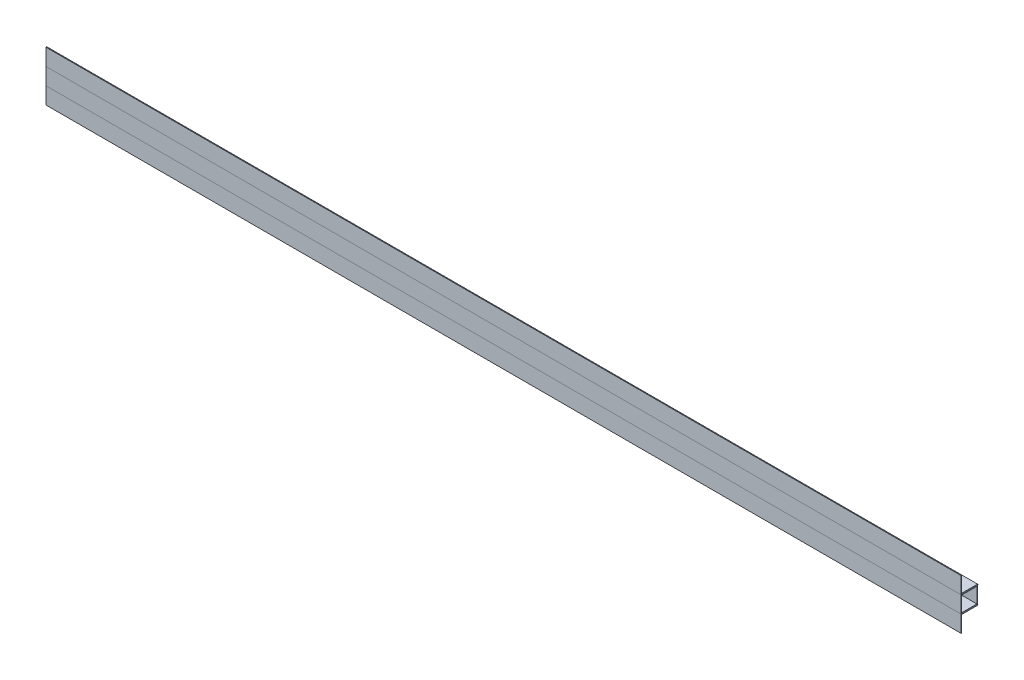
SolidWorks part; units mm, degrees
ref_plane "Front Plane" through (0, 0, 0) normal (0, 0, 1) x (1, 0, 0)
ref_plane "Top Plane" through (0, 0, 0) normal (0, 1, 0) x (1, 0, 0)
ref_plane "Right Plane" through (0, 0, 0) normal (1, 0, 0) x (0, 0, -1)
sketch3d "3DSketch1"
  line L0 (0, 0, 0) -> (1392.0499, 0, 0)
  dimension "D1" = 1392.0499
other "Squre tube 1X1SQUARE TUBE(1)"
ref_plane "Plane1" through (0, 0, 0) normal (1, 0, 0) x (0, 0, -1)
sketch "Sketch1" plane through (0, 0, 0) normal (1, 0, 0) x (0, 0, -1)
  line L0 (-11.7, 11.7) -> (11.7, 11.7)
  line L1 (-12.7, 12.7) -> (12.7, 12.7)
  line L2 (-12.7, 12.7) -> (-12.7, -12.7)
  line L3 (-12.7, -12.7) -> (12.7, -12.7)
  line L4 (12.7, 12.7) -> (12.7, -12.7)
  line L5 (0, -12.7) -> (0, 12.7) construction
  line L6 (-12.7, 0) -> (12.7, 0) construction
  line L7 (11.7, 11.7) -> (11.7, -11.7)
  line L8 (-11.7, -11.7) -> (11.7, -11.7)
  line L9 (-11.7, 11.7) -> (-11.7, -11.7)
  point P0 (0, 0)
  point P8 (0, 0)
  point P9 (0, -12.7)
  point P10 (0, 12.7)
  point P11 (0, 0)
  dimension "D1" = 25.4
  dimension "D2" = 25.4
  dimension "D3" = 1
ref_plane "Plane2" through (0, 12.7, 0) normal (0, 1, 0) x (1, 0, 0)
sketch3d "3DSketch3"
  line L0 (0, 12.7, 0) -> (1392.0499, 12.7, 0)
  line L1 (0, 12.7, -12.7) -> (0, 12.7, 12.7) construction
  line L2 (1392.0499, 12.7, -12.7) -> (1392.0499, 12.7, 12.7) construction
other "Angleiron ANGLE IRON ONE BY ONE INCH 2ND FILE(1)"
ref_plane "Plane3" through (0, 12.7, 12.7) normal (1, 0, 0) x (0, 0, -1)
sketch "Sketch13" plane through (0, 12.7, 12.7) normal (1, 0, 0) x (0, 0, -1)
  line L0 (1.25, 25.4) -> (1.25, 1.25)
  line L1 (1.25, 1.25) -> (25.4, 1.25)
  line L3 (25.4, 0) -> (0, 0)
  line L4 (0, 0) -> (0, 25.4)
  line L6 (0.625, 26.025) -> (0, 25.4)
  line L7 (0.625, 26.025) -> (1.25, 25.4)
  line L10 (26.025, 0.625) -> (25.4, 1.25)
  line L11 (26.025, 0.625) -> (25.4, 0)
  point P0 (12.7, 0)
  point P2 (0, 12.7)
  point P4 (0, 0)
  dimension "D1" = 90
  dimension "D2" = 90
  dimension "D3" = 1.25
  dimension "D4" = 1.25
  dimension "D5" = 25.4
  dimension "D6" = 25.4
sketch3d "3DSketch4"
  line L0 (0, -12.7, 0) -> (1392.0499, -12.7, 0)
  line L1 (1392.0499, -12.7, 12.7) -> (1392.0499, -12.7, -12.7) construction
other "Angleiron ANGLE IRON ONE BY ONE INCH 2ND FILE(2)"
ref_plane "Plane4" through (0, -12.7, 12.7) normal (-1, 0, 0) x (0, 0, -1)
sketch "Sketch14" plane through (0, -12.7, 12.7) normal (-1, 0, 0) x (0, 0, -1)
  line L0 (1.25, 25.4) -> (1.25, 1.25)
  line L1 (1.25, 1.25) -> (25.4, 1.25)
  line L3 (25.4, 0) -> (0, 0)
  line L4 (0, 0) -> (0, 25.4)
  line L6 (0.625, 26.025) -> (0, 25.4)
  line L7 (0.625, 26.025) -> (1.25, 25.4)
  line L10 (26.025, 0.625) -> (25.4, 1.25)
  line L11 (26.025, 0.625) -> (25.4, 0)
  point P0 (12.7, 0)
  point P2 (0, 12.7)
  point P4 (0, 0)
  dimension "D1" = 90
  dimension "D2" = 90
  dimension "D3" = 1.25
  dimension "D4" = 1.25
  dimension "D5" = 25.4
  dimension "D6" = 25.4
